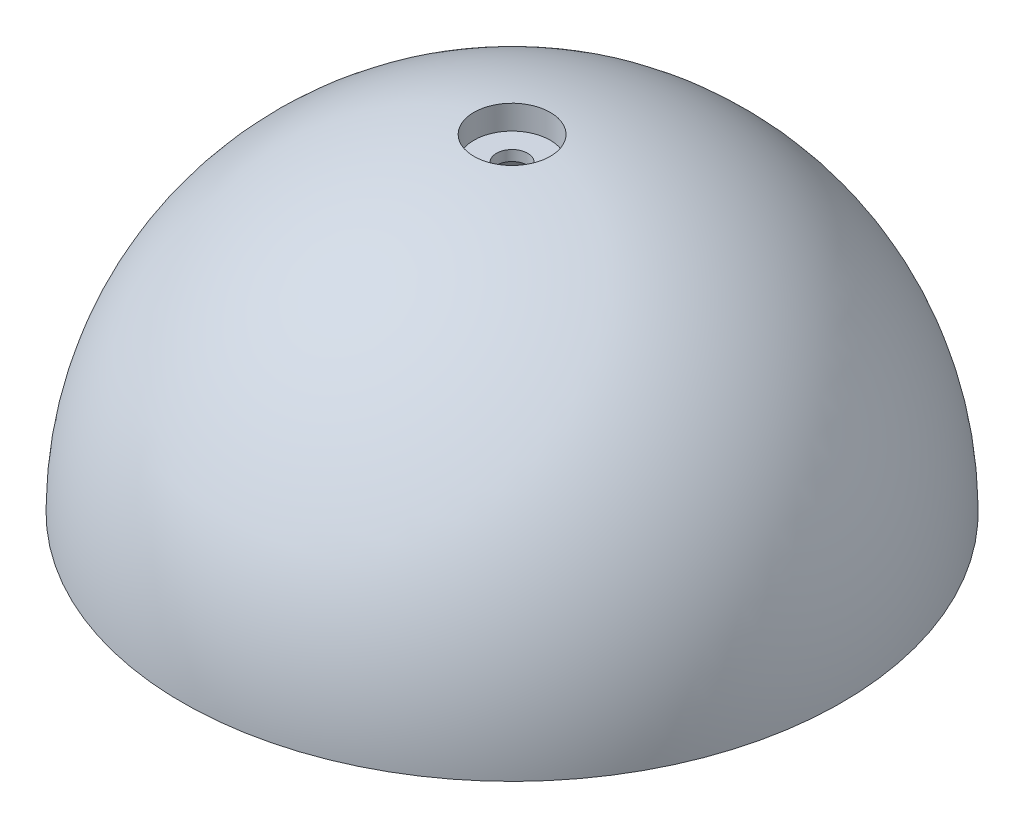
SolidWorks part; units mm, degrees
ref_plane "Front Plane" through (0, 0, 0) normal (0, 0, 1) x (1, 0, 0)
ref_plane "Top Plane" through (0, 0, 0) normal (0, 1, 0) x (1, 0, 0)
ref_plane "Right Plane" through (0, 0, 0) normal (1, 0, 0) x (0, 0, -1)
sketch "Half Circle" plane through (0, 0, 0) normal (0, 0, 1) x (1, 0, 0)
  line L2 (0, 85) -> (0, 95)
  line L3 (0, -85) -> (0, -95)
  line L4 (0, -85) -> (0, 85) construction
  arc A0 (0, 95) -> (0, -95) centre (0, 0) ccw
  arc A1 (0, 85) -> (0, -85) centre (0, 0) ccw
  dimension "D1" = 190
  dimension "D2" = 10
revolve "Sphere Revolve" add sketch "Half Circle" angle 360 about L2
sketch "Sketch2" plane through (0, 0, 0) normal (0, 1, 0) x (1, 0, 0)
  line L1 (-121.3228, -115.569) -> (121.3228, -115.569)
  line L2 (-121.3228, -115.569) -> (-121.3228, 115.569)
  line L3 (-121.3228, 115.569) -> (121.3228, 115.569)
  line L4 (121.3228, -115.569) -> (121.3228, 115.569)
  line L5 (-121.3228, -115.569) -> (121.3228, 115.569) construction
  line L6 (-121.3228, 115.569) -> (121.3228, -115.569) construction
  point P0 (0, 0)
extrude "Cut in Half" cut sketch "Sketch2" against normal through all
sketch "Sketch3" plane through (0, 0, 0) normal (0, 1, 0) x (1, 0, 0)
  line L0 (0, -95) -> (0, 95) construction
  circle A0 centre (0, 0) radius 11
  circle A1 centre (0, 0) radius 95 construction
  dimension "D1" = 22
  dimension "D2" = 190
extrude "BallBearingHole" cut sketch "Sketch3" along normal through all
ref_plane "SupportForHolePlane" through (0, 84.4, 0) normal (0, 1, 0) x (1, 0, 0)
sketch "Sketch4" plane through (0, 84.4, 0) normal (0, 1, 0) x (1, 0, 0)
  circle A0 centre (0, 0) radius 31.2029
extrude "SupportForHole" add sketch "Sketch4" along normal blind 4
ref_plane "TopPlane" through (0, 94.4, 0) normal (0, 1, 0) x (1, 0, 0)
sketch "Sketch5" plane through (0, 94.4, 0) normal (0, 1, 0) x (1, 0, 0)
  circle A1 centre (0, 0) radius 11
  circle A2 centre (0, 0) radius 11 construction
extrude "2ndBearingHole" cut sketch "Sketch5" against normal blind 7
sketch "Sketch6" plane through (0, 87.4, 0) normal (0, 1, 0) x (1, 0, 0)
  circle A0 centre (0, 0) radius 4.5
  dimension "D1" = 9
extrude "InsideHole" cut sketch "Sketch6" against normal through all
